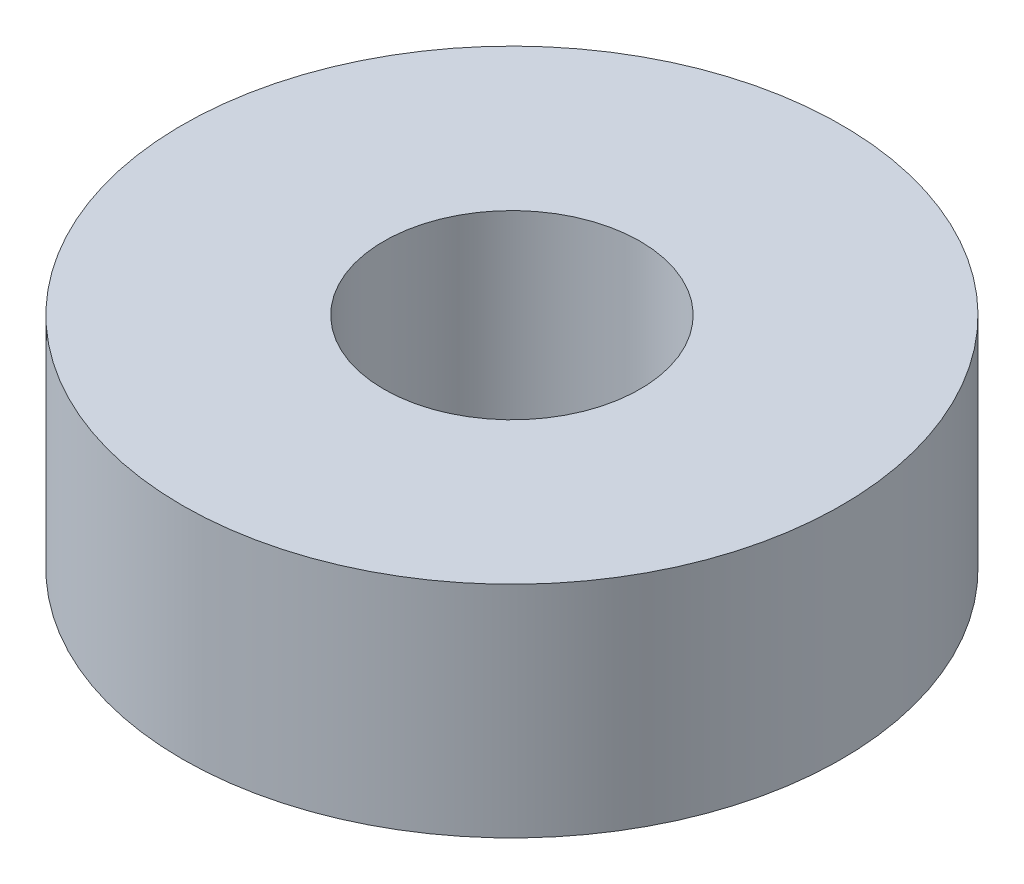
SolidWorks part; units mm, degrees
ref_plane "前视基准面" through (0, 0, 0) normal (0, 0, 1) x (1, 0, 0)
ref_plane "上视基准面" through (0, 0, 0) normal (0, 1, 0) x (1, 0, 0)
ref_plane "右视基准面" through (0, 0, 0) normal (1, 0, 0) x (0, 0, -1)
other "Configuration Table"
sketch "草图2" plane through (0, 0, 0) normal (0, 1, 0) x (1, 0, 0)
  circle A18 centre (0, 0) radius 4.5
  circle A19 centre (0, 0) radius 1.75
  dimension "D1" = 3.5
  dimension "D2" = 9
extrude "凸台-拉伸1" add sketch "草图2" along normal blind 3
